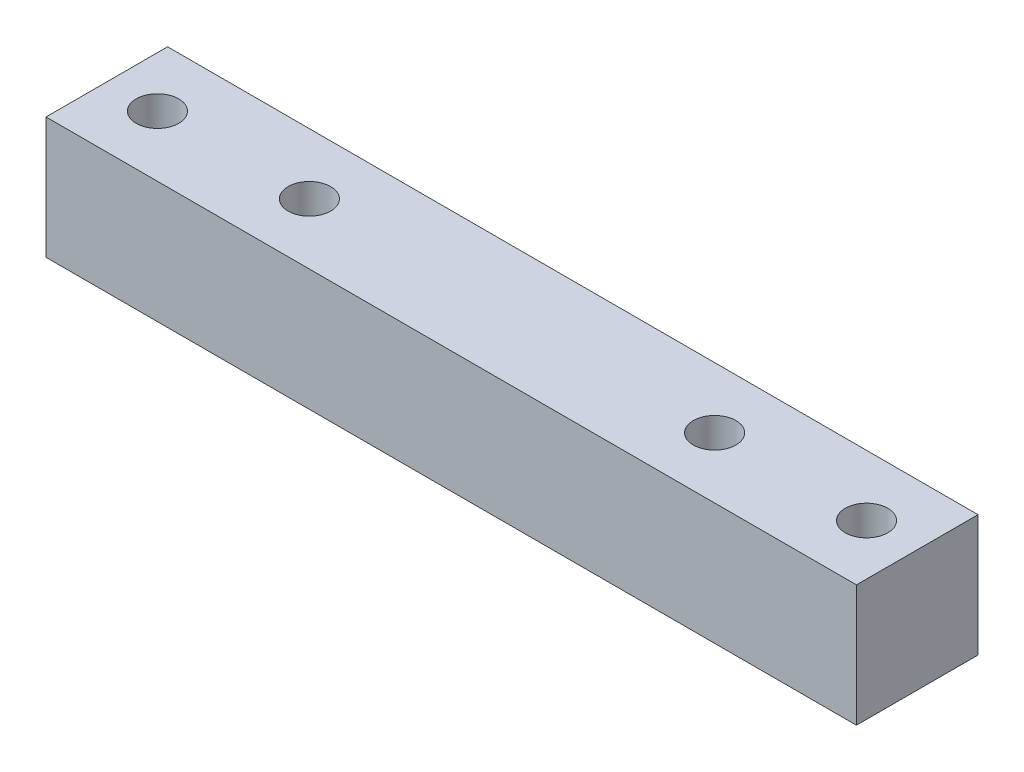
SolidWorks part; units mm, degrees
material "Ductile Iron (SN)"
ref_plane "Front Plane" through (0, 0, 0) normal (0, 0, 1) x (1, 0, 0)
ref_plane "Top Plane" through (0, 0, 0) normal (0, 1, 0) x (1, 0, 0)
ref_plane "Right Plane" through (0, 0, 0) normal (1, 0, 0) x (0, 0, -1)
sketch "Sketch1" plane through (0, 0, 0) normal (0, 1, 0) x (1, 0, 0)
  line L1 (40, -6) -> (-40, -6)
  line L2 (40, -6) -> (40, 6)
  line L3 (40, 6) -> (-40, 6)
  line L4 (-40, -6) -> (-40, 6)
  line L5 (40, -6) -> (-40, 6) construction
  line L6 (40, 6) -> (-40, -6) construction
  point P0 (0, 0)
  dimension "D1" = 80
  dimension "D2" = 12
extrude "Boss-Extrude1" add sketch "Sketch1" along normal blind 12
sketch "Sketch2" plane through (0, 12, 0) normal (0, 1, 0) x (1, 0, 0)
  line L0 (-35, 0) -> (35, 0) construction
  line L1 (40, -6) -> (40, 6) construction
  line L2 (0, 6) -> (0, -6) construction
  line L3 (40, 6) -> (-40, 6) construction
  line L4 (-40, -6) -> (40, -6) construction
  circle A0 centre (35, 0) radius 2.1
  circle A1 centre (20, 0) radius 2.1
  circle A2 centre (-20, 0) radius 2.1
  circle A3 centre (-35, 0) radius 2.1
  dimension "D2" = 4.2
  dimension "D1" = 5
  dimension "D3" = 15
extrude "Cut-Extrude1" cut sketch "Sketch2" against normal through all
sketch "Sketch3" plane through (-40, 0, 0) normal (-1, 0, 0) x (0, 0, 1)
  line L0 (-3, 0) -> (0, 10.9635)
  line L1 (-6, 0) -> (6, 0) construction
  line L3 (0, 10.9635) -> (3, 0)
  line L4 (3, 0) -> (-3, 0)
  dimension "D1" = 6
extrude "Cut-Extrude8" cut sketch "Sketch3" against normal blind 0.2
